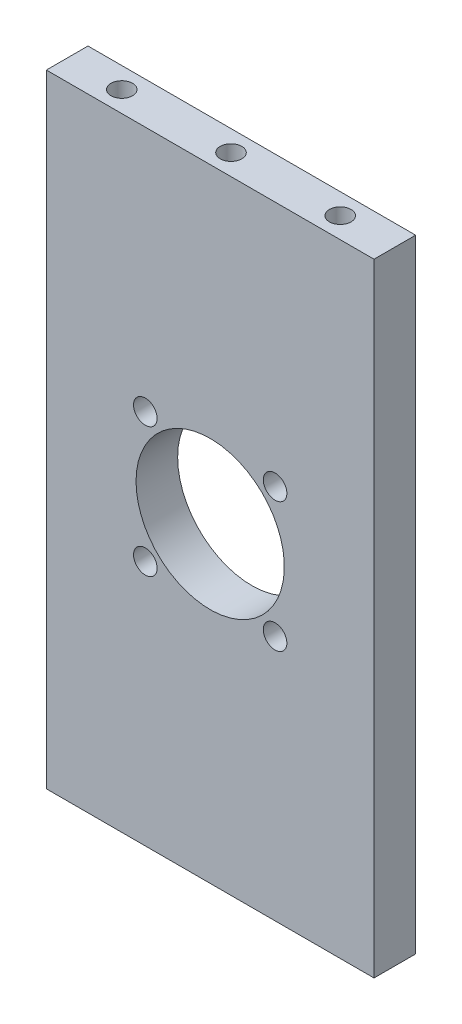
SolidWorks part; units mm, degrees
ref_plane "Front Plane" through (0, 0, 0) normal (0, 0, 1) x (1, 0, 0)
ref_plane "Top Plane" through (0, 0, 0) normal (0, 1, 0) x (1, 0, 0)
ref_plane "Right Plane" through (0, 0, 0) normal (1, 0, 0) x (0, 0, -1)
sketch "Sketch1" plane through (0, 0, 0) normal (0, 0, 1) x (1, 0, 0)
  line L1 (-25, -47.5) -> (25, -47.5)
  line L2 (-25, -47.5) -> (-25, 47.5)
  line L3 (-25, 47.5) -> (25, 47.5)
  line L4 (25, -47.5) -> (25, 47.5)
  line L5 (-25, -47.5) -> (25, 47.5) construction
  line L6 (-25, 47.5) -> (25, -47.5) construction
  point P0 (0, 0)
  dimension "D1" = 95
  dimension "D2" = 50
extrude "Boss-Extrude1" add sketch "Sketch1" against normal blind 6.35
sketch "Sketch2" plane through (0, 47.5, 0) normal (0, 1, 0) x (1, 0, 0)
  point P0 (-16.67, 3.175)
  point P1 (0, 3.175)
  point P2 (16.67, 3.175)
  dimension "D1" = 3.175
  dimension "D2" = 16.67
  dimension "D3" = 16.67
sketch "Sketch3" plane through (0, -47.5, 0) normal (0, -1, 0) x (1, 0, 0)
  line L4 (25, 0) -> (-25, 0)
  line L5 (-25, 0) -> (-25, -6.35)
  line L6 (-25, -6.35) -> (25, -6.35)
  line L7 (25, -6.35) -> (25, 0)
  line L8 (25, 0) -> (-25, 0) construction
  line L9 (-25, 0) -> (-25, -6.35) construction
  line L10 (-25, -6.35) -> (25, -6.35) construction
  line L11 (25, -6.35) -> (25, 0) construction
  point P2 (16.67, -3.175)
  point P6 (0, -3.175)
  point P7 (-16.67, -3.175)
  dimension "D1" = 0
hole_wizard "M4x0.7 Tapped Hole1" positions "Sketch3" profile "Sketch5" tap size "M4x0.7" standard "ANSI Metric"
sketch "Sketch5" plane through (-16.67, -47.5, -3.175) normal (1, 0, 0) x (0, 0, -1)
  line L0 (0, 0) -> (0, 10.9914)
  line L1 (0, 10.9914) -> (1.65, 10)
  line L2 (1.65, 10) -> (1.65, 0)
  line L5 (1.65, 0) -> (0, 0)
  line L10 (0, 10.9914) -> (-1.65, 10) construction
  line L11 (0, -6.35) -> (0, 107.95) construction
  dimension "Tap Drill Dia." = 3.3
  dimension "Tap Drill Depth" = 10
  dimension "Drill Angle" = 118
hole_wizard "M4x0.7 Tapped Hole2" positions "Sketch2" profile "Sketch6" tap size "M4x0.7" standard "ANSI Metric"
sketch "Sketch6" plane through (-16.67, 47.5, -3.175) normal (1, 0, 0) x (0, 0, 1)
  line L0 (0, 0) -> (0, 10.9914)
  line L1 (0, 10.9914) -> (1.65, 10)
  line L2 (1.65, 10) -> (1.65, 0)
  line L5 (1.65, 0) -> (0, 0)
  line L10 (0, 10.9914) -> (-1.65, 10) construction
  line L11 (0, -6.35) -> (0, 107.95) construction
  dimension "Tap Drill Dia." = 3.3
  dimension "Tap Drill Depth" = 10
  dimension "Drill Angle" = 118
sketch "Sketch7" plane through (0, 0, -6.35) normal (0, 0, -1) x (-1, 0, 0)
  circle A0 centre (0, 0) radius 11.3175
  dimension "D1" = 22.635
extrude "Cut-Extrude1" cut sketch "Sketch7" against normal through all
sketch "Sketch8" plane through (0, 0, -6.35) normal (0, 0, -1) x (-1, 0, 0)
  line L0 (0, 0) -> (9.8995, 9.8995) construction
  line L1 (0, 0) -> (0, 14) construction
  circle A0 centre (0, 0) radius 14 construction
  point P3 (9.8995, 9.8995)
  point P9 (9.8995, -9.8995)
  point P10 (-9.8995, -9.8995)
  point P11 (-9.8995, 9.8995)
  point P12 (0, 0)
  dimension "D1" = 28
  dimension "D2" = 45
  dimension "D3" = 4
hole_wizard "M3 Clearance Hole1" positions "Sketch8" profile "Sketch9" hole size "M3" standard "ANSI Metric" end condition through all
sketch "Sketch9" plane through (9.8995, 9.8995, -6.35) normal (1, 0, 0) x (0, 1, 0)
  line L0 (0, 0) -> (0, 6.35)
  line L1 (0, 6.35) -> (1.8, 6.35)
  line L2 (1.8, 6.35) -> (1.8, 0)
  line L5 (1.8, 0) -> (0, 0)
  line L11 (0, -6.35) -> (0, 107.95) construction
  dimension "Thru Hole Dia." = 3.6
  dimension "Thru Hole Depth" = 6.35
